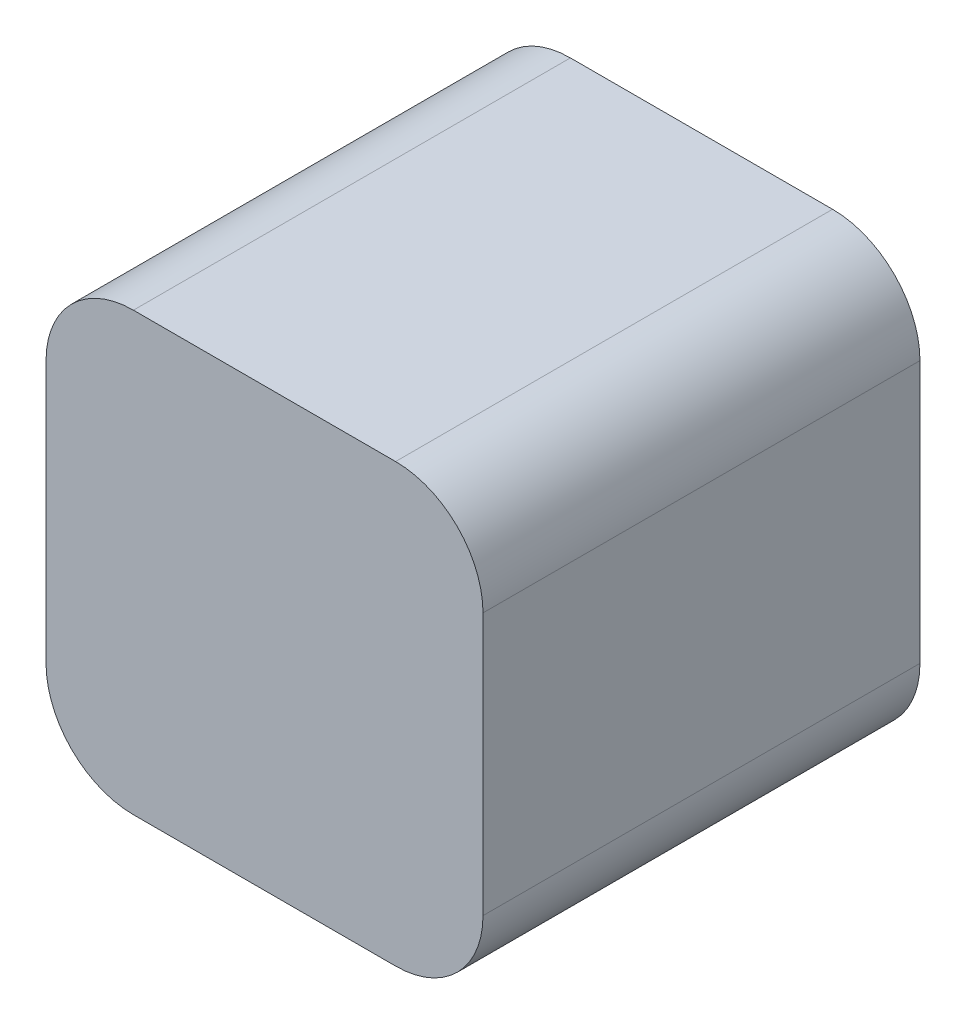
SolidWorks part; units mm, degrees
ref_plane "Front Plane" through (0, 0, 0) normal (0, 0, 1) x (1, 0, 0)
ref_plane "Top Plane" through (0, 0, 0) normal (0, 1, 0) x (1, 0, 0)
ref_plane "Right Plane" through (0, 0, 0) normal (1, 0, 0) x (0, 0, -1)
sketch "Sketch1" plane through (0, 0, 0) normal (0, 0, 1) x (1, 0, 0)
  line L1 (-7.5, 7.5) -> (7.5, 7.5)
  line L2 (-7.5, 7.5) -> (-7.5, -7.5)
  line L3 (-7.5, -7.5) -> (7.5, -7.5)
  line L4 (7.5, 7.5) -> (7.5, -7.5)
  line L5 (-7.5, 7.5) -> (7.5, -7.5) construction
  line L6 (-7.5, -7.5) -> (7.5, 7.5) construction
  point P0 (0, 0)
  dimension "D1" = 15
extrude "Boss-Extrude1" add sketch "Sketch1" along normal blind 15
fillet "Fillet1" radius 3 4 edges at (7.5, 7.5, 7.5) (7.5, -7.5, 7.5) (-7.5, 7.5, 7.5) (-7.5, -7.5, 7.5)
